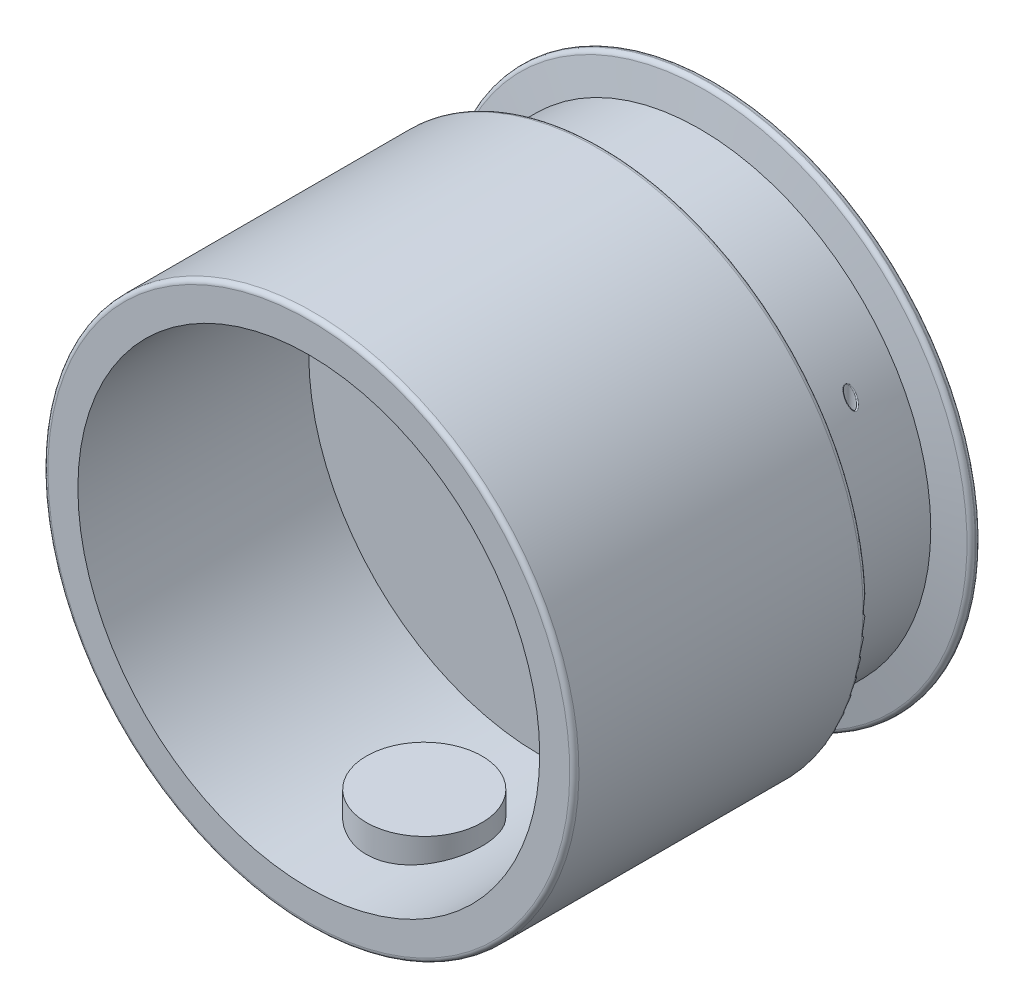
SolidWorks part; units mm, degrees
ref_plane "Front" through (0, 0, 0) normal (0, 0, 1) x (1, 0, 0)
ref_plane "Top" through (0, 0, 0) normal (0, 1, 0) x (1, 0, 0)
ref_plane "Right" through (0, 0, 0) normal (1, 0, 0) x (0, 0, -1)
sketch "Sketch3" plane through (0, 0, 0) normal (1, 0, 0) x (0, 0, -1)
  line L0 (5.588, 1.7145) -> (-5.588, 1.7145)
  line L1 (-5.588, 1.7145) -> (-5.588, 7.3025)
  line L2 (-5.588, 7.3025) -> (2.4581, 7.3025)
  line L3 (2.4581, 7.3025) -> (2.626, 6.35)
  line L4 (5.334, 7.3025) -> (5.588, 7.3025)
  line L5 (3.896, 6.35) -> (3.896, 8.1999) construction
  line L7 (5.588, 7.3025) -> (5.588, 1.7145)
  line L8 (0, 0) -> (0, 1.7145) construction
  line L9 (0, 0) -> (-5.4492, 0) construction
  line L10 (5.334, 7.3025) -> (5.166, 6.35)
  line L11 (5.166, 6.35) -> (2.626, 6.35)
  dimension "D1" = 12.7
  dimension "D2" = 3.429
  dimension "D3" = 100
  dimension "D4" = 0.254
  dimension "D5" = 14.605
  dimension "D6" = 11.176
  dimension "D7" = 2.54
revolve "Revolve1" add sketch "Sketch3" angle 360 about L9
sketch "Sketch4" plane through (0, 0, 0) normal (0, 0, 1) x (1, 0, 0)
  line L0 (-1.5164, 0.8001) -> (1.5164, 0.8001)
  line L1 (0, 0.8001) -> (0, -1.7145) construction
  circle A0 centre (0, 0) radius 1.7145 construction
  arc A1 (1.5164, 0.8001) -> (-1.5164, 0.8001) centre (0, 0) ccw
  point P5 (0, 0.8001)
  dimension "D1" = 2.5146
extrude "Boss-Extrude1" add sketch "Sketch4" along normal up to surface and the other way up to surface up to face at (0, 1.7145, 5.588) other way up to face at (0, 7.3025, -5.588)
fillet "Fillet2" radius 0.127 4 edges at (0, 7.3025, -2.4581) (0, 7.3025, 5.588) (0, 7.3025, -5.334) (0, 7.3025, -5.588)
sketch "Sketch5" plane through (0, 0, 5.588) normal (0, 0, 1) x (1, 0, 0)
  circle A0 centre (0, 0) radius 6.35
  dimension "D1" = 12.7
extrude "Cut-Extrude1" cut sketch "Sketch5" against normal blind 6.35
chamfer "Chamfer1" distance 0.254 angle 45 2 edges at (0, -1.7145, -5.588) (0, 0.8001, -5.588)
sketch "Sketch7" plane through (0, 0, 0) normal (0, 1, 0) x (1, 0, 0)
  line L0 (0, 0.762) -> (0, -5.588) construction
  line L1 (-6.35, -5.588) -> (6.35, -5.588) construction
  line L2 (-6.35, 0.762) -> (6.35, 0.762) construction
  circle A0 centre (0, -2.413) radius 1.5875
  dimension "D1" = 3.175
extrude "Boss-Extrude2" add sketch "Sketch7" against normal up to surface (0.762 mm away) from offset 5.588 offset against normal yes
sketch "Sketch8" plane through (0, 0, 0) normal (0, 1, 0) x (1, 0, 0)
  line L0 (5.3975, 3.896) -> (7.3025, 3.896) construction
  line L3 (7.3025, 5.4406) -> (7.3025, 5.461) construction
  circle A0 centre (5.3975, 3.896) radius 0.127
  point P0 (5.5245, 3.896)
  dimension "D1" = 0.254
  dimension "D2" = 1.905
extrude "Cut-Extrude3" cut sketch "Sketch8" against normal through all and the other way through all
fillet "Fillet4" radius 0.0254 2 edges at (5.4049, -3.3331, -4.0228) (5.3561, 3.411, -4.0161)
